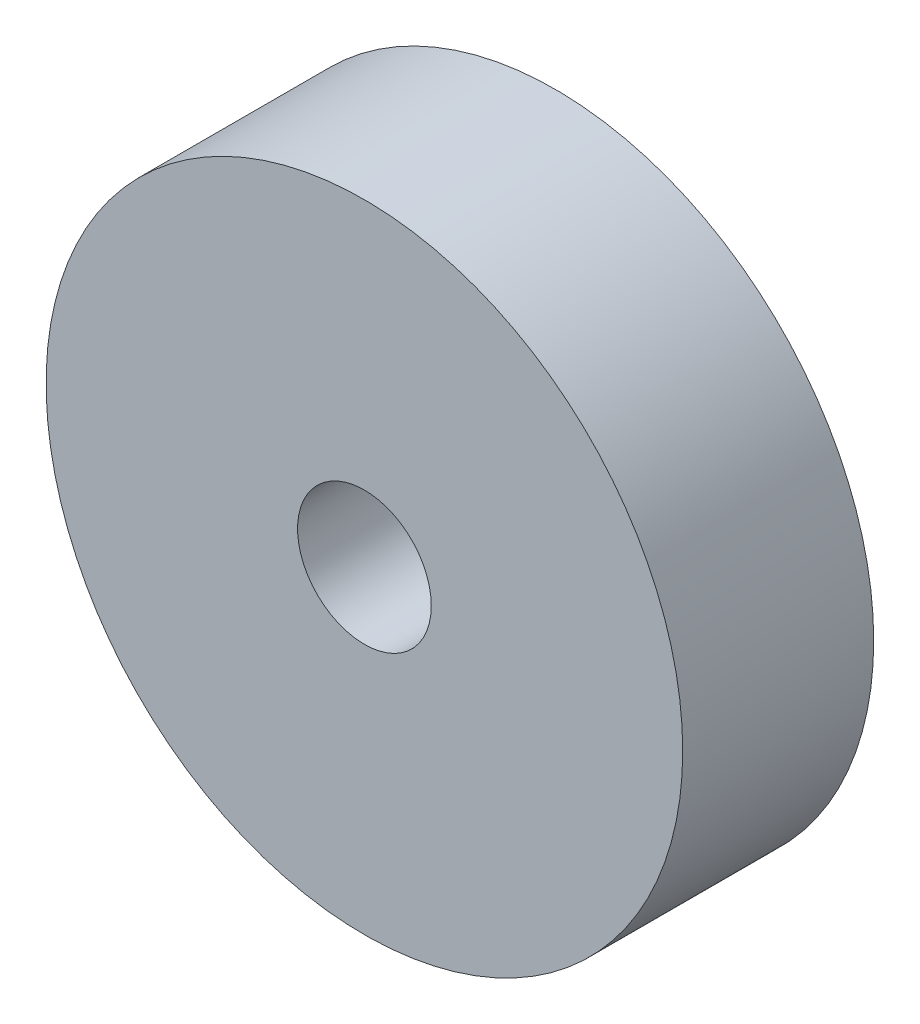
SolidWorks part; units mm, degrees
material "ABS"
ref_plane "前视基准面" through (0, 0, 0) normal (0, 0, 1) x (1, 0, 0)
ref_plane "上视基准面" through (0, 0, 0) normal (0, 1, 0) x (1, 0, 0)
ref_plane "右视基准面" through (0, 0, 0) normal (1, 0, 0) x (0, 0, -1)
other "Configuration Table"
sketch "草图1" plane through (0, 0, 0) normal (0, 0, 1) x (1, 0, 0)
  circle A0 centre (0, 0) radius 2.1
  circle A1 centre (0, 0) radius 10
  dimension "D1" = 4.2
  dimension "D2" = 20
extrude "凸台-拉伸1" add sketch "草图1" along normal blind 6
